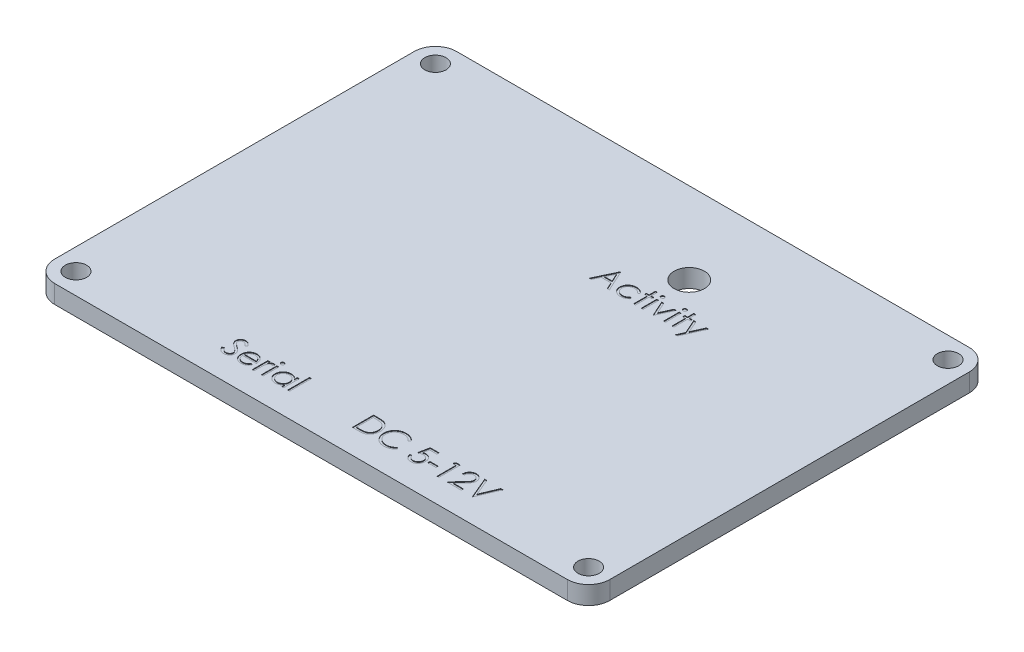
SolidWorks part; units mm, degrees
ref_plane "Plan de face" through (0, 0, 0) normal (0, 0, 1) x (1, 0, 0)
ref_plane "Plan de dessus" through (0, 0, 0) normal (0, 1, 0) x (1, 0, 0)
ref_plane "Plan de droite" through (0, 0, 0) normal (1, 0, 0) x (0, 0, -1)
sketch "Esquisse1" plane through (0, 0, 0) normal (0, 1, 0) x (1, 0, 0)
  line L0 (-45.735, -33.115) -> (-45.735, 33.115)
  line L1 (-38.735, -31.115) -> (38.735, -31.115) construction
  line L2 (-38.735, -31.115) -> (-38.735, 31.115) construction
  line L3 (-38.735, 31.115) -> (38.735, 31.115) construction
  line L4 (38.735, -31.115) -> (38.735, 31.115) construction
  line L5 (-38.735, -31.115) -> (38.735, 31.115) construction
  line L6 (-38.735, 31.115) -> (38.735, -31.115) construction
  line L7 (-45.735, 33.115) -> (45.735, 33.115)
  line L8 (45.735, 33.115) -> (45.735, -33.115)
  line L9 (45.735, -33.115) -> (-45.735, -33.115)
  point P0 (0, 0)
  dimension "D1" = 77.47
  dimension "D2" = 62.23
  dimension "D3" = 7
  dimension "D4" = 2
  dimension "D5" = 7
  dimension "D6" = 2
extrude "Boss.-Extru.1" add sketch "Esquisse1" along normal blind 3
sketch "Esquisse2" plane through (0, 3, 0) normal (0, 1, 0) x (1, 0, 0)
  line L0 (-45.735, 33.115) -> (45.735, 33.115) construction
  line L1 (-45.735, -33.115) -> (-45.735, 33.115) construction
  line L2 (45.735, -33.115) -> (-45.735, -33.115) construction
  line L3 (45.735, 33.115) -> (45.735, -33.115) construction
  circle A0 centre (-42.235, 29.615) radius 1.75
  circle A1 centre (42.235, 29.615) radius 1.75
  circle A2 centre (42.235, -29.615) radius 1.75
  circle A3 centre (-42.235, -29.615) radius 1.75
  dimension "D3" = 3.5
  dimension "D1" = 3.5
  dimension "D2" = 3.5
  dimension "D4" = 3.5
  dimension "D5" = 3.5
  dimension "D6" = 3.5
  dimension "D7" = 3.5
  dimension "D8" = 3.5
  dimension "D9" = 3.5
extrude "Enlèv. mat.-Extru.1" cut sketch "Esquisse2" against normal through all
sketch "Esquisse3" plane through (0, 3, 0) normal (0, 1, 0) x (1, 0, 0)
  line L0 (-38.735, 31.115) -> (38.735, 31.115) construction
  line L1 (38.735, -31.115) -> (38.735, 31.115) construction
  circle A0 centre (9.525, 19.685) radius 2.5
  dimension "D3" = 5
  dimension "D1" = 11.43
  dimension "D2" = 29.21
extrude "Enlèv. mat.-Extru.2" cut sketch "Esquisse3" against normal through all
fillet "Congé1" radius 3.5 4 edges at (-45.735, 1.5, -33.115) (45.735, 1.5, -33.115) (45.735, 1.5, 33.115) (-45.735, 1.5, 33.115)
sketch "Esquisse4" plane through (0, 3, 0) normal (0, 1, 0) x (1, 0, 0)
  line L0 (9.525, 19.685) -> (9.525, 11.685) construction
  line L1 (-1.8311, 11.685) -> (20.8811, 11.685) construction
  line L2 (-22.5623, -29.115) -> (-4.1077, -29.115) construction
  line L5 (0.9353, -29.115) -> (25.7347, -29.115) construction
  line L6 (-13.335, -29.115) -> (-13.335, -31.115) construction
  line L7 (13.335, -29.115) -> (13.335, -31.115) construction
  line L8 (-38.735, -31.115) -> (38.735, -31.115) construction
  line L9 (-38.735, -31.115) -> (-38.735, 31.115) construction
  line L10 (38.735, -31.115) -> (38.735, 31.115) construction
  text T0 "Activity"
  text T1 "Serial"
  text T2 "DC 5-12V"
  point P5 (9.525, 11.685)
  point P15 (0, 0)
  point P18 (0, 0)
  point P19 (-25.2509, -26.0713)
  point P20 (-1.8311, 10.7377)
  point P21 (10.8427, -27.5184)
  point P22 (9.525, -29.115)
  point P23 (7.4492, -29.115)
  dimension "D1" = 8
  dimension "D2" = 2
  dimension "D3" = 2
  dimension "D4" = 25.4
  dimension "D5" = 25.4
extrude "Enlèv. mat.-Extru.3" cut sketch "Esquisse4" against normal blind 0.1
